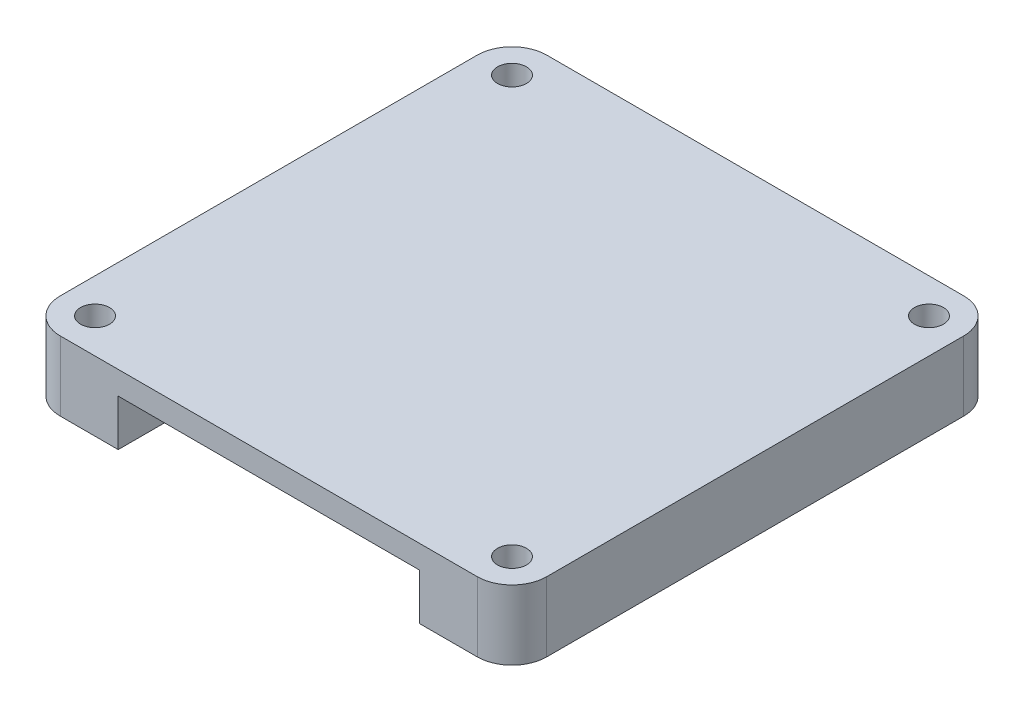
SolidWorks part; units mm, degrees
ref_plane "前视基准面" through (0, 0, 0) normal (0, 0, 1) x (1, 0, 0)
ref_plane "上视基准面" through (0, 0, 0) normal (0, 1, 0) x (1, 0, 0)
ref_plane "右视基准面" through (0, 0, 0) normal (1, 0, 0) x (0, 0, -1)
sketch "草图1" plane through (0, 0, 0) normal (0, 1, 0) x (1, 0, 0)
  line L1 (0, 0) -> (36, 0) construction
  line L2 (0, 0) -> (0, 36) construction
  line L3 (0, 36) -> (36, 36) construction
  line L4 (36, 0) -> (36, 36) construction
  line L5 (0, -3) -> (36, -3)
  line L6 (-3, 0) -> (-3, 36)
  line L7 (0, 39) -> (36, 39)
  line L8 (39, 0) -> (39, 36)
  circle A0 centre (0, 36) radius 1.25
  circle A1 centre (36, 36) radius 1.25
  circle A2 centre (0, 0) radius 1.25
  circle A3 centre (36, 0) radius 1.25
  arc A4 (36, -3) -> (39, 0) centre (36, 0) ccw
  arc A5 (0, -3) -> (-3, 0) centre (0, 0) cw
  arc A6 (36, 39) -> (39, 36) centre (36, 36) cw
  arc A7 (-3, 36) -> (0, 39) centre (0, 36) cw
  dimension "D3" = 2.5
  dimension "D8" = 3
  dimension "D1" = 36
  dimension "D2" = 36
  dimension "D4" = 3
  dimension "D5" = 3
  dimension "D6" = 3
  dimension "D7" = 3
extrude "凸台-拉伸1" add sketch "草图1" along normal blind 2
sketch "草图2" plane through (0, 0, 0) normal (0, -1, 0) x (1, 0, 0)
  line L0 (39, 0) -> (39, -36) construction
  line L1 (-3, -36) -> (-3, 0) construction
  line L2 (39, 0) -> (39, -36)
  line L3 (-3, -36) -> (-3, 0)
  line L4 (5, 3) -> (0, 3)
  line L5 (0, 3) -> (36, 3) construction
  line L6 (5, -39) -> (0, -39)
  line L7 (36, -39) -> (0, -39) construction
  line L8 (5, -39) -> (5, 3)
  line L9 (36, 3) -> (31, 3)
  line L10 (31, 3) -> (31, -39)
  line L11 (31, -39) -> (36, -39)
  arc A0 (39, 0) -> (36, 3) centre (36, 0) ccw construction
  arc A1 (36, -39) -> (39, -36) centre (36, -36) ccw construction
  arc A2 (-3, -36) -> (0, -39) centre (0, -36) ccw construction
  arc A3 (0, 3) -> (-3, 0) centre (0, 0) ccw construction
  circle A4 centre (0, -36) radius 1.25 construction
  circle A5 centre (36, -36) radius 1.25 construction
  circle A6 centre (36, 0) radius 1.25 construction
  circle A7 centre (0, 0) radius 1.25 construction
  arc A8 (39, 0) -> (36, 3) centre (36, 0) ccw
  arc A9 (36, -39) -> (39, -36) centre (36, -36) ccw
  arc A10 (-3, -36) -> (0, -39) centre (0, -36) ccw
  arc A11 (0, 3) -> (-3, 0) centre (0, 0) ccw
  circle A12 centre (0, -36) radius 1.25
  circle A13 centre (36, -36) radius 1.25
  circle A14 centre (36, 0) radius 1.25
  circle A15 centre (0, 0) radius 1.25
  dimension "D1" = 5
  dimension "D2" = 5
extrude "凸台-拉伸2" add sketch "草图2" along normal blind 4
